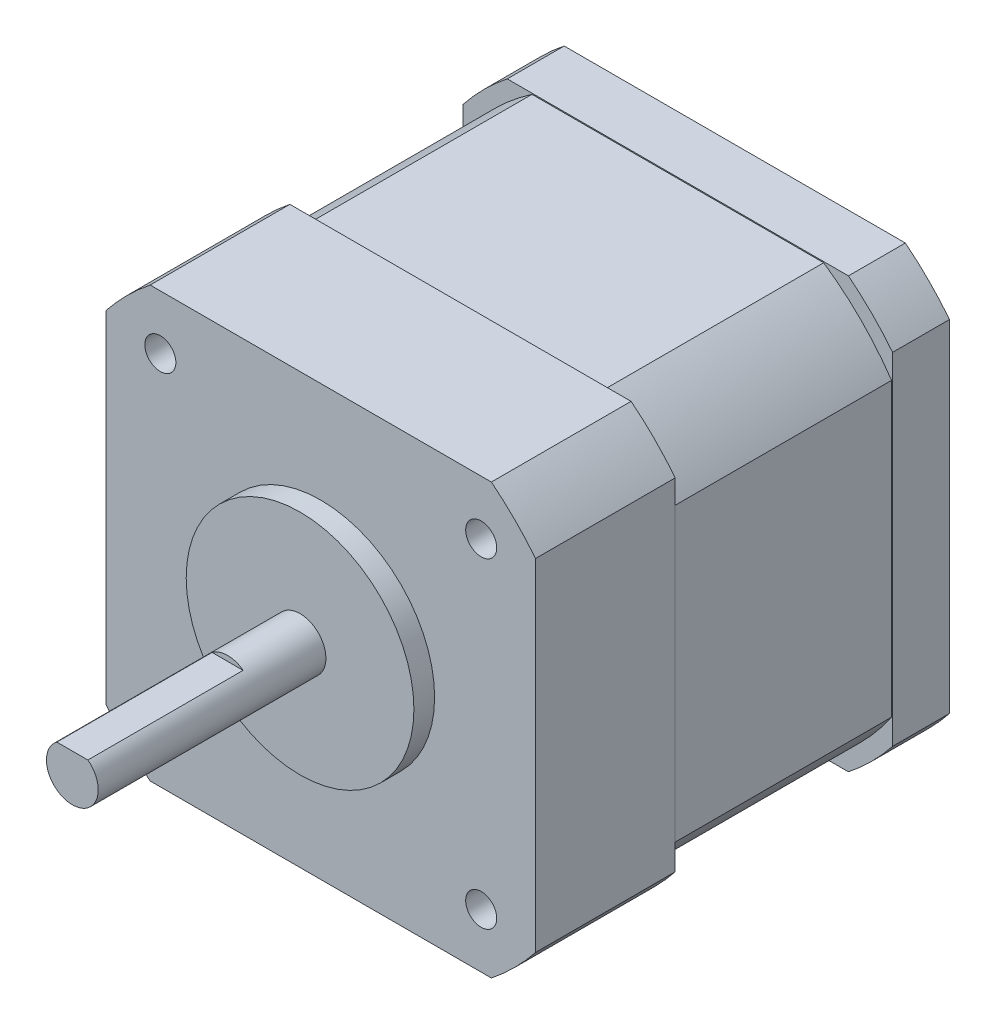
SolidWorks part; units mm, degrees
material "Plain Carbon Steel"
ref_plane "Front" through (0, 0, 0) normal (0, 0, 1) x (1, 0, 0)
ref_plane "Top" through (0, 0, 0) normal (0, 1, 0) x (1, 0, 0)
ref_plane "Right" through (0, 0, 0) normal (1, 0, 0) x (0, 0, -1)
sketch "Sketch1" plane through (0, 0, 0) normal (0, 0, 1) x (1, 0, 0)
  circle A0 centre (0, 0) radius 2.5
  dimension "D1" = 5
extrude "Boss-Extrude1" add sketch "Sketch1" along normal blind 24
sketch "Sketch2" plane through (0, 0, 0) normal (0, 0, -1) x (-1, 0, 0)
  circle A0 centre (0, 0) radius 11
  dimension "D1" = 22
extrude "Boss-Extrude2" add sketch "Sketch2" against normal blind 2
sketch "Sketch3" plane through (0, 0, 0) normal (0, 0, -1) x (-1, 0, 0)
  line L1 (20.75, -20.75) -> (-20.75, -20.75)
  line L2 (20.75, -20.75) -> (20.75, 20.75)
  line L3 (20.75, 20.75) -> (-20.75, 20.75)
  line L4 (-20.75, -20.75) -> (-20.75, 20.75)
  line L5 (20.75, -20.75) -> (-20.75, 20.75) construction
  line L6 (20.75, 20.75) -> (-20.75, -20.75) construction
  point P0 (0, 0)
  dimension "D1" = 41.5
extrude "Boss-Extrude3" add sketch "Sketch3" along normal blind 40
sketch "Sketch4" plane through (0, 0, -40) normal (0, 0, -1) x (-1, 0, 0)
  line L0 (-20.75, -16.4829) -> (-20.75, -20.75)
  line L1 (16.4829, -20.75) -> (20.75, -20.75)
  line L2 (20.75, 16.4829) -> (20.75, 20.75)
  line L3 (-16.4829, 20.75) -> (-20.75, 20.75)
  line L4 (-20.75, 20.75) -> (-20.75, -20.75)
  line L5 (-20.75, -20.75) -> (20.75, -20.75)
  line L6 (20.75, -20.75) -> (20.75, 20.75)
  line L7 (20.75, 20.75) -> (-20.75, 20.75)
  line L8 (-20.75, 20.75) -> (-20.75, 16.4829)
  line L9 (-20.75, -20.75) -> (-16.4829, -20.75)
  line L10 (20.75, -20.75) -> (20.75, -16.4829)
  line L11 (20.75, 20.75) -> (16.4829, 20.75)
  arc A0 (-20.75, -16.4829) -> (-16.4829, -20.75) centre (0, 0) ccw
  arc A1 (16.4829, -20.75) -> (20.75, -16.4829) centre (0, 0) ccw
  arc A2 (20.75, 16.4829) -> (16.4829, 20.75) centre (0, 0) ccw
  arc A3 (-16.4829, 20.75) -> (-20.75, 16.4829) centre (0, 0) ccw
  dimension "D2" = 26.5
  dimension "D1" = 0
extrude "Cut-Extrude1" cut sketch "Sketch4" against normal through all both and the other way through all
hole_wizard "M3x0.5 Tapped Hole1" positions "Sketch6" profile "Sketch5" tap size "M3x0.5" standard "ANSI Metric"
sketch "Sketch6" plane through (0, 0, 0) normal (0, 0, 1) x (1, 0, 0)
  line L0 (-16.1632, 0) -> (0, 0) construction
  line L1 (0, 0) -> (0, 15.0764) construction
  point P0 (-15.5, 15.5)
  point P11 (-15.5, -15.5)
  point P12 (15.5, -15.5)
  point P13 (15.5, 15.5)
  dimension "D1" = 31
  dimension "D2" = 31
sketch "Sketch5" plane through (-15.5, 15.5, 0) normal (1, 0, 0) x (0, -1, 0)
  line L0 (0, 0) -> (0, 8.2511)
  line L1 (0, 8.2511) -> (1.25, 7.5)
  line L2 (1.25, 7.5) -> (1.25, 6)
  line L3 (1.25, 6) -> (1.5, 6)
  line L4 (1.5, 6) -> (1.5, 0)
  line L5 (1.5, 0) -> (0, 0)
  line L10 (0, 8.2511) -> (-1.25, 7.5) construction
  line L11 (0, -6.35) -> (0, 107.95) construction
  dimension "Tap Drill Dia." = 2.5
  dimension "Tap Drill Depth" = 7.5
  dimension "Thread Major Dia." = 3
  dimension "Thread Depth" = 6
  dimension "Drill Angle" = 118
sketch "Sketch7" plane through (0, 0, 24) normal (0, 0, 1) x (1, 0, 0)
  line L0 (-1.5, 2) -> (1.5, 2)
  circle A0 centre (0, 0) radius 2.5 construction
  circle A1 centre (0, 0) radius 2.5 construction
  arc A2 (1.5, 2) -> (-1.5, 2) centre (0, 0) ccw
  dimension "D1" = 4.5
extrude "Cut-Extrude2" cut sketch "Sketch7" against normal blind 15
ref_plane "Plane1" through (0, 0, -24) normal (0, 0, 1) x (1, 0, 0)
sketch "Sketch8" plane through (0, 0, -24) normal (0, 0, 1) x (1, 0, 0)
  line L0 (-14.0918, 20.65) -> (14.0918, 20.65)
  line L1 (-5.7152, 0) -> (0, 0) construction
  line L2 (0, 0) -> (0, 8.4579) construction
  line L3 (-16.4829, 20.75) -> (16.4829, 20.75) construction
  line L4 (-14.0918, -20.65) -> (14.0918, -20.65)
  line L5 (-20.65, 14.0918) -> (-20.65, -14.0918)
  line L6 (-20.75, -16.4829) -> (-20.75, 16.4829) construction
  line L7 (20.65, 14.0918) -> (20.65, -14.0918)
  line L12 (16.4829, 20.75) -> (-16.4829, 20.75)
  line L13 (-20.75, 16.4829) -> (-20.75, -16.4829)
  line L14 (-16.4829, -20.75) -> (16.4829, -20.75)
  line L15 (20.75, -16.4829) -> (20.75, 16.4829)
  line L16 (16.4829, 20.75) -> (-16.4829, 20.75)
  line L17 (-20.75, 16.4829) -> (-20.75, -16.4829)
  line L18 (-16.4829, -20.75) -> (16.4829, -20.75)
  line L19 (20.75, -16.4829) -> (20.75, 16.4829)
  arc A0 (-14.0918, 20.65) -> (-20.65, 14.0918) centre (0, 0) ccw
  arc A1 (-20.65, -14.0918) -> (-14.0918, -20.65) centre (0, 0) ccw
  arc A2 (20.65, 14.0918) -> (14.0918, 20.65) centre (0, 0) ccw
  arc A3 (14.0918, -20.65) -> (20.65, -14.0918) centre (0, 0) ccw
  arc A5 (-16.4829, 20.75) -> (-20.75, 16.4829) centre (0, 0) ccw
  arc A6 (-20.75, -16.4829) -> (-16.4829, -20.75) centre (0, 0) ccw
  arc A7 (16.4829, -20.75) -> (20.75, -16.4829) centre (0, 0) ccw
  arc A8 (20.75, 16.4829) -> (16.4829, 20.75) centre (0, 0) ccw
  arc A9 (-16.4829, 20.75) -> (-20.75, 16.4829) centre (0, 0) ccw
  arc A10 (-20.75, -16.4829) -> (-16.4829, -20.75) centre (0, 0) ccw
  arc A11 (16.4829, -20.75) -> (20.75, -16.4829) centre (0, 0) ccw
  arc A12 (20.75, 16.4829) -> (16.4829, 20.75) centre (0, 0) ccw
  dimension "D1" = 50
  dimension "D2" = 0.1
  dimension "D3" = 0.1
  dimension "D4" = 0
extrude "Cut-Extrude3" cut sketch "Sketch8" against normal mid plane 21
